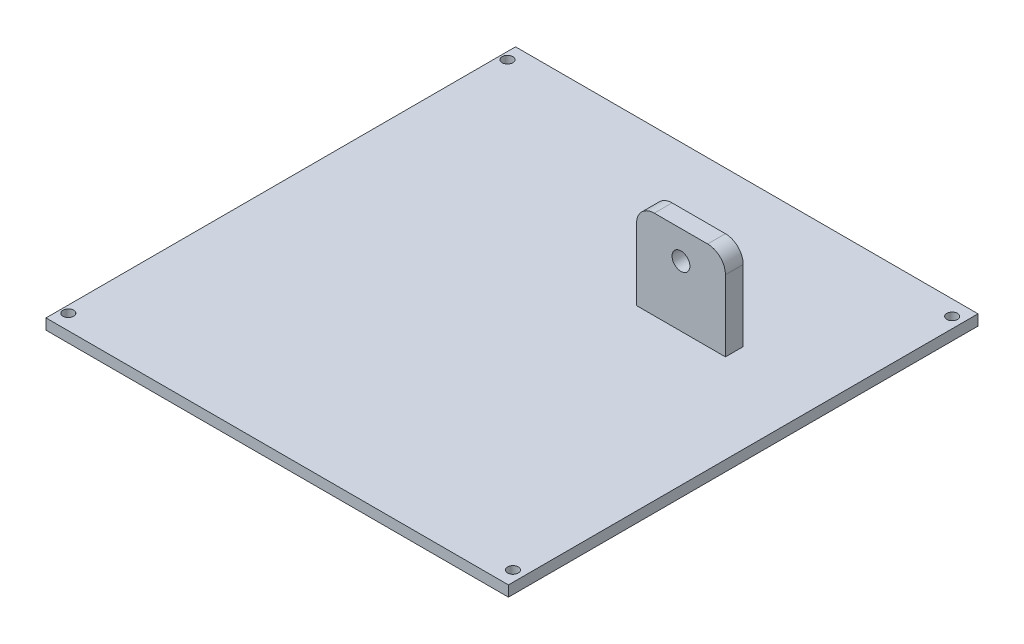
SolidWorks part; units mm, degrees
ref_plane "Front Plane" through (0, 0, 0) normal (0, 0, 1) x (1, 0, 0)
ref_plane "Top Plane" through (0, 0, 0) normal (0, 1, 0) x (1, 0, 0)
ref_plane "Right Plane" through (0, 0, 0) normal (1, 0, 0) x (0, 0, -1)
sketch "Sketch1" plane through (0, 0, 0) normal (0, 1, 0) x (1, 0, 0)
  line L1 (-65, 66) -> (65, 66)
  line L2 (-65, 66) -> (-65, -66)
  line L3 (-65, -66) -> (65, -66)
  line L4 (65, 66) -> (65, -66)
  line L5 (-65, 66) -> (65, -66) construction
  line L6 (-65, -66) -> (65, 66) construction
  point P0 (0, 0)
  dimension "D1" = 132
  dimension "D2" = 130
extrude "Boss-Extrude1" add sketch "Sketch1" along normal blind 3
sketch "Sketch2" plane through (0, 3, 0) normal (0, 1, 0) x (1, 0, 0)
  line L0 (-70.4184, 0) -> (70.6004, 0) construction
  line L2 (15, 20) -> (40, 20)
  line L3 (15, 20) -> (15, 25)
  line L4 (15, 25) -> (40, 25)
  line L5 (40, 20) -> (40, 25)
  point P7 (0, 0)
  dimension "D1" = 25
  dimension "D2" = 5
  dimension "D3" = 15
  dimension "D4" = 20
extrude "Boss-Extrude2" add sketch "Sketch2" along normal blind 25
fillet "Fillet1" radius 5 2 edges at (40, 28, -22.5) (15, 28, -22.5)
sketch "Sketch3" plane through (0, 0, -20) normal (0, 0, 1) x (1, 0, 0)
  circle A0 centre (27.5, 20.0647) radius 2.5
  dimension "D1" = 5
extrude "Cut-Extrude1" cut sketch "Sketch3" against normal blind 25
sketch "Sketch4" plane through (0, 3, 0) normal (0, 1, 0) x (1, 0, 0)
  line L0 (-65, 66) -> (-65, -66) construction
  line L1 (-63, 61.73) -> (-63, -61.73) construction
  circle A0 centre (-63, 61.73) radius 1.5
  circle A1 centre (62, 61.73) radius 1.5
  circle A2 centre (-63, -61.73) radius 1.5
  circle A3 centre (62, -61.73) radius 1.5
  point P10 (-63, 0)
  point P11 (0, 0)
  dimension "D1" = 3
  dimension "D2" = 125
  dimension "D3" = 2
  dimension "D4" = 123.46
extrude "Cut-Extrude2" cut sketch "Sketch4" against normal blind 25
